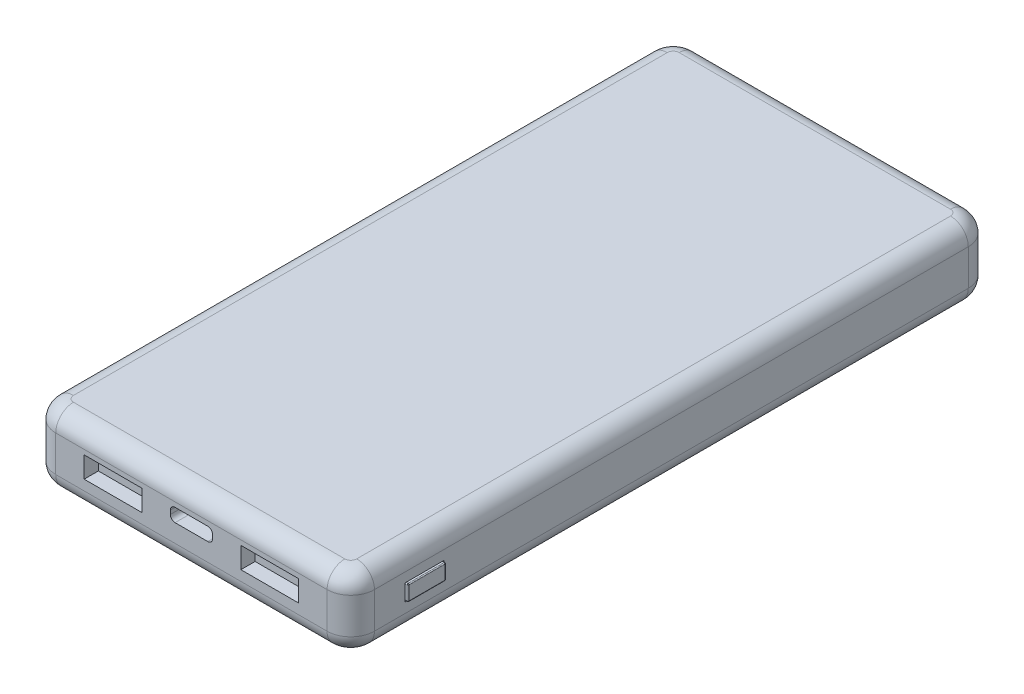
SolidWorks part; units mm, degrees
ref_plane "Front Plane" through (0, 0, 0) normal (0, 0, 1) x (1, 0, 0)
ref_plane "Top Plane" through (0, 0, 0) normal (0, 1, 0) x (1, 0, 0)
ref_plane "Right Plane" through (0, 0, 0) normal (1, 0, 0) x (0, 0, -1)
sketch "Sketch1" plane through (0, 0, 0) normal (0, 1, 0) x (1, 0, 0)
  line L0 (0, 0) -> (67.3, 0)
  line L1 (67.3, 0) -> (67.3, 135.4)
  line L2 (67.3, 135.4) -> (0, 135.4)
  line L3 (0, 135.4) -> (0, 0)
  dimension "D1" = 135.4
  dimension "D2" = 67.3
extrude "Boss-Extrude1" add sketch "Sketch1" along normal blind 15.1
fillet "Fillet1" radius 5 4 edges at (0, 7.55, -135.4) (67.3, 7.55, -135.4) (67.3, 7.55, 0) (0, 7.55, 0)
fillet "Fillet2" radius 3.75 8 edges at (1.4645, 15.1, -1.4645) (0, 15.1, -67.7) (1.4645, 15.1, -133.9355) (33.65, 15.1, -135.4) (65.8355, 15.1, -133.9355) (67.3, 15.1, -67.7) (65.8355, 15.1, -1.4645) (33.65, 15.1, 0)
sketch "Sketch2" plane through (0, 0, 0) normal (0, 0, 1) x (1, 0, 0)
  line L0 (11, 5.9) -> (11, 10.35)
  line L1 (11, 10.35) -> (23.2, 10.35)
  line L2 (23.2, 10.35) -> (23.2, 5.9)
  line L3 (23.2, 5.9) -> (11, 5.9)
  line L4 (33.65, 0) -> (33.65, 18.9371) construction
  line L5 (5, 0) -> (62.3, 0) construction
  line L7 (56.3, 5.9) -> (56.3, 10.35)
  line L8 (44.1, 10.35) -> (44.1, 5.9)
  line L9 (56.3, 10.35) -> (44.1, 10.35)
  line L10 (44.1, 5.9) -> (56.3, 5.9)
  line L11 (30.2, 7.55) -> (37.1, 7.55)
  line L12 (29.2, 8.55) -> (29.2, 9.35)
  line L13 (30.2, 10.35) -> (37.1, 10.35)
  line L14 (38.1, 9.35) -> (38.1, 8.55)
  line L15 (62.3, 11.35) -> (5, 11.35) construction
  arc A0 (37.1, 10.35) -> (38.1, 9.35) centre (37.1, 9.35) cw
  arc A1 (38.1, 8.55) -> (37.1, 7.55) centre (37.1, 8.55) cw
  arc A2 (30.2, 10.35) -> (29.2, 9.35) centre (30.2, 9.35) ccw
  arc A3 (30.2, 7.55) -> (29.2, 8.55) centre (30.2, 8.55) cw
  point P18 (33.65, 7.55)
  point P23 (38.1, 7.55)
  point P26 (29.2, 10.35)
  point P29 (29.2, 7.55)
  dimension "D8" = 1
  dimension "D1" = 1
  dimension "D2" = 6
  dimension "D3" = 12.2
  dimension "D4" = 4.45
  dimension "D5" = 8.9
  dimension "D6" = 1
  dimension "D7" = 2.8
extrude "Cut-Extrude1" cut sketch "Sketch2" against normal blind 3
sketch "Sketch3" plane through (67.3, 0, 0) normal (1, 0, 0) x (0, 0, -1)
  line L1 (11.5, 5.85) -> (19.7, 5.85)
  line L2 (11.5, 5.85) -> (11.5, 9.35)
  line L3 (11.5, 9.35) -> (19.7, 9.35)
  line L4 (19.7, 5.85) -> (19.7, 9.35)
  line L5 (11.6, 5.95) -> (19.6, 5.95)
  line L6 (11.6, 5.95) -> (11.6, 9.25)
  line L7 (11.6, 9.25) -> (19.6, 9.25)
  line L8 (19.6, 5.95) -> (19.6, 9.25)
  line L9 (130.4, 11.35) -> (5, 11.35) construction
  line L10 (0, 0) -> (0, 11.35) construction
  dimension "D1" = 11.5
  dimension "D2" = 0.1
  dimension "D3" = 0.1
  dimension "D4" = 8.2
  dimension "D5" = 3.5
  dimension "D6" = 2
  dimension "D7" = 0.1
  dimension "D8" = 0.1
extrude "Cut-Extrude2" cut sketch "Sketch3" against normal blind 3
fillet "Fillet3" radius 3.75 8 edges at (1.4645, 0, -1.4645) (0, 0, -67.7) (1.4645, 0, -133.9355) (33.65, 0, -135.4) (65.8355, 0, -133.9355) (67.3, 0, -67.7) (65.8355, 0, -1.4645) (33.65, 0, 0)
sketch "Sketch4" plane through (67.3, 0, 0) normal (1, 0, 0) x (0, 0, -1)
  line L0 (11.6, 9.25) -> (19.6, 9.25)
  line L1 (19.6, 9.25) -> (19.6, 5.95)
  line L2 (19.6, 5.95) -> (11.6, 5.95)
  line L3 (11.6, 5.95) -> (11.6, 9.25)
extrude "Boss-Extrude2" add sketch "Sketch4" along normal blind 0.5
fillet "Fillet4" radius 0.2 4 edges at (66.05, 5.95, -11.6) (66.05, 5.95, -19.6) (66.05, 9.25, -19.6) (66.05, 9.25, -11.6)
fillet "Fillet5" radius 0.2 8 edges at (67.8, 9.1914, -19.5414) (67.8, 7.6, -19.6) (67.8, 6.0086, -19.5414) (67.8, 5.95, -15.6) (67.8, 6.0086, -11.6586) (67.8, 7.6, -11.6) (67.8, 9.1914, -11.6586) (67.8, 9.25, -15.6)
